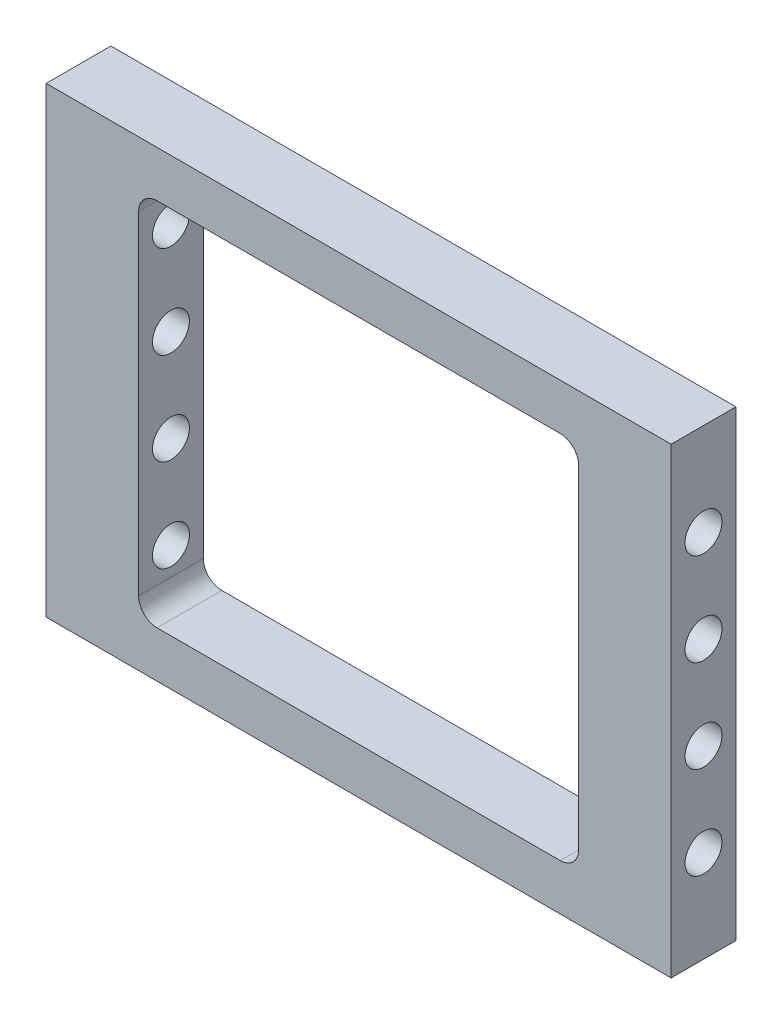
SolidWorks part; units mm, degrees
ref_plane "前视基准面" through (0, 0, 0) normal (0, 0, 1) x (1, 0, 0)
ref_plane "上视基准面" through (0, 0, 0) normal (0, 1, 0) x (1, 0, 0)
ref_plane "右视基准面" through (0, 0, 0) normal (1, 0, 0) x (0, 0, -1)
sketch "草图1" plane through (0, 0, 0) normal (0, 0, 1) x (1, 0, 0)
  line L1 (0, 0) -> (67.6, 0)
  line L2 (0, 0) -> (0, 50)
  line L3 (0, 50) -> (67.6, 50)
  line L4 (67.6, 0) -> (67.6, 50)
  dimension "D1" = 50
  dimension "D2" = 67.6
extrude "凸台-拉伸1" add sketch "草图1" along normal blind 7
sketch "草图2" plane through (0, 0, 0) normal (-1, 0, 0) x (0, 0, 1)
  line L0 (7, 50) -> (7, 0) construction
  line L1 (7, 0) -> (0, 0) construction
  circle A0 centre (3.5, 40) radius 2
  circle A1 centre (3.5, 30) radius 2
  circle A2 centre (3.5, 20) radius 2
  circle A3 centre (3.5, 10) radius 2
  dimension "D1" = 4
  dimension "D2" = 4
  dimension "D3" = 4
  dimension "D4" = 4
  dimension "D5" = 10
  dimension "D8" = 3.5
  dimension "D9" = 10
  dimension "D6" = 10
  dimension "D7" = 10
extrude "切除-拉伸1" cut sketch "草图2" against normal blind 10
ref_plane "基准面1" through (33.8, 0, 0) normal (1, 0, 0) x (0, 0, -1)
mirror "镜向1" about plane through (33.8, 0, 0) normal (1, 0, 0) of "切除-拉伸1"
sketch "草图3" plane through (0, 0, 7) normal (0, 0, 1) x (1, 0, 0)
  line L0 (67.6, 50) -> (0, 50) construction
  line L1 (10, 45) -> (57.6, 45)
  line L2 (10, 45) -> (10, 5)
  line L3 (10, 5) -> (57.6, 5)
  line L4 (57.6, 45) -> (57.6, 5)
  line L9 (0, 50) -> (0, 0) construction
  dimension "D1" = 40
  dimension "D2" = 5
  dimension "D3" = 47.6
  dimension "D4" = 10
extrude "切除-拉伸2" cut sketch "草图3" against normal blind 7
fillet "圆角1" radius 2 4 edges at (57.6, 5, 3.5) (57.6, 45, 3.5) (10, 5, 3.5) (10, 45, 3.5)
